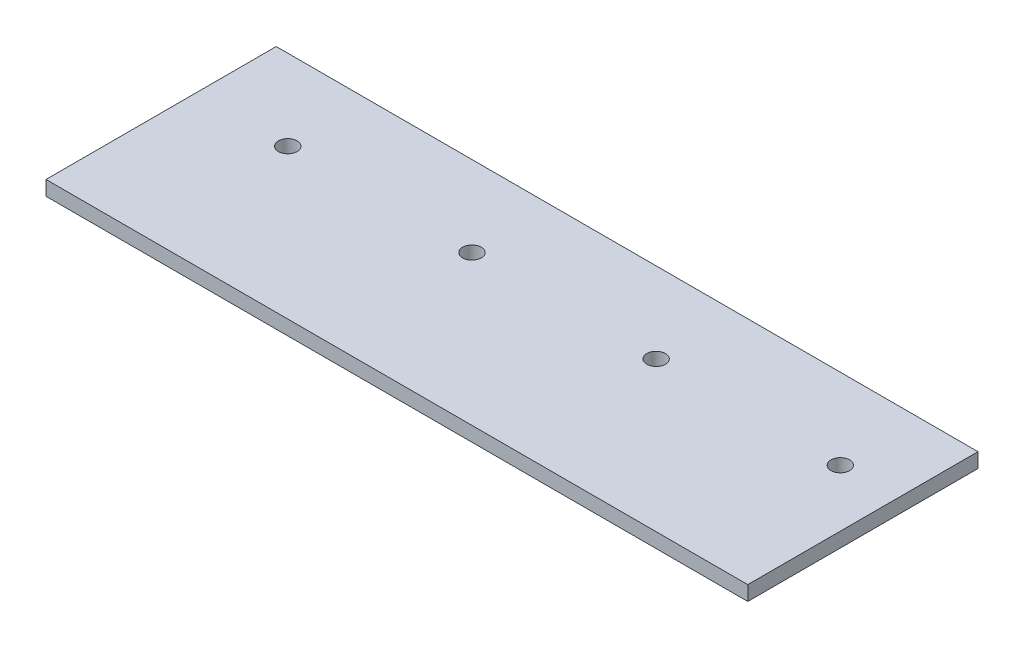
SolidWorks part; units mm, degrees
ref_plane "Front Plane" through (0, 0, 0) normal (0, 0, 1) x (1, 0, 0)
ref_plane "Top Plane" through (0, 0, 0) normal (0, 1, 0) x (1, 0, 0)
ref_plane "Right Plane" through (0, 0, 0) normal (1, 0, 0) x (0, 0, -1)
sketch "Sketch1" plane through (0, 0, 0) normal (0, 1, 0) x (1, 0, 0)
  line L0 (0, 65) -> (304.8, 65) construction
  line L1 (0, 100) -> (304.8, 100)
  line L2 (0, 100) -> (0, 0)
  line L3 (0, 0) -> (304.8, 0)
  line L4 (304.8, 100) -> (304.8, 0)
  circle A0 centre (40, 65) radius 4.05
  circle A1 centre (120, 65) radius 4.05
  circle A2 centre (200, 65) radius 4.05
  circle A3 centre (280, 65) radius 4.05
  dimension "D5" = 8.1
  dimension "D1" = 100
  dimension "D2" = 304.8
  dimension "D3" = 35
  dimension "D4" = 40
  dimension "D6" = 4
extrude "Boss-Extrude1" add sketch "Sketch1" against normal blind 6.35
